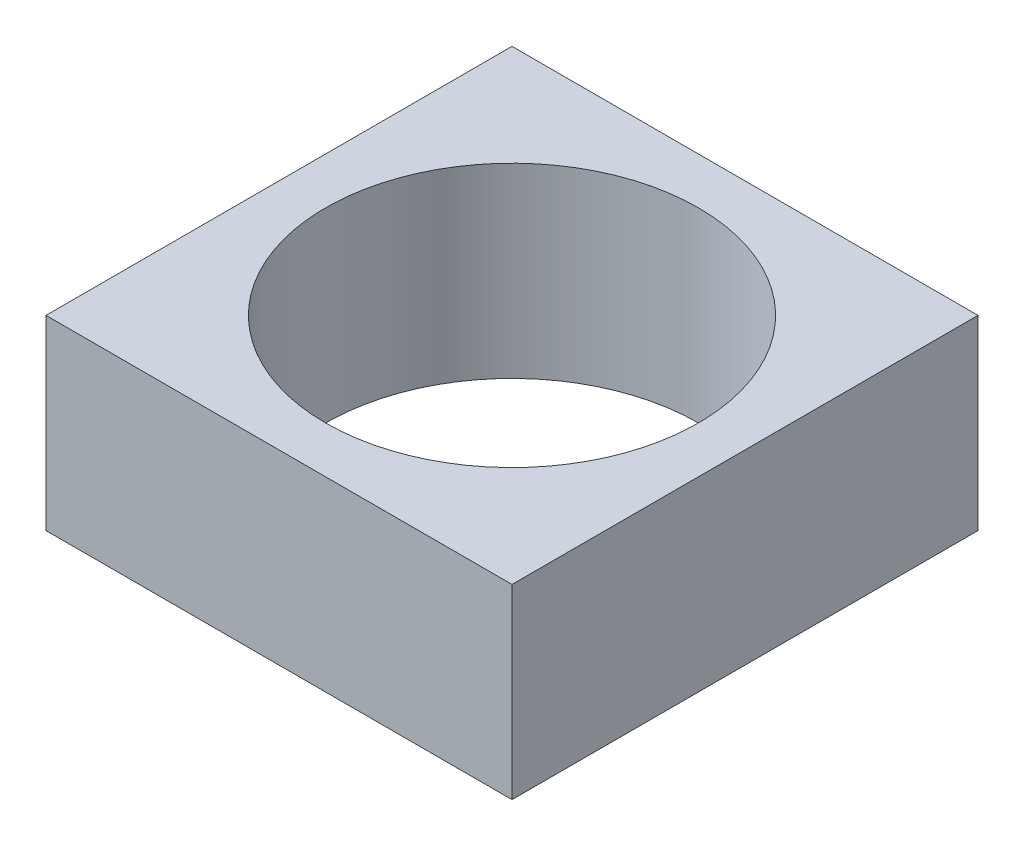
SolidWorks part; units mm, degrees
ref_plane "Front Plane" through (0, 0, 0) normal (0, 0, 1) x (1, 0, 0)
ref_plane "Top Plane" through (0, 0, 0) normal (0, 1, 0) x (1, 0, 0)
ref_plane "Right Plane" through (0, 0, 0) normal (1, 0, 0) x (0, 0, -1)
sketch "Sketch1" plane through (0, 0, 0) normal (0, 1, 0) x (1, 0, 0)
  line L1 (-25, -25) -> (25, -25)
  line L2 (-25, -25) -> (-25, 25)
  line L3 (-25, 25) -> (25, 25)
  line L4 (25, -25) -> (25, 25)
  line L5 (-25, -25) -> (25, 25) construction
  line L6 (-25, 25) -> (25, -25) construction
  circle A0 centre (0, 0) radius 20
  point P0 (0, 0)
  dimension "D2" = 40
  dimension "D1" = 50
extrude "Boss-Extrude1" add sketch "Sketch1" along normal blind 20
